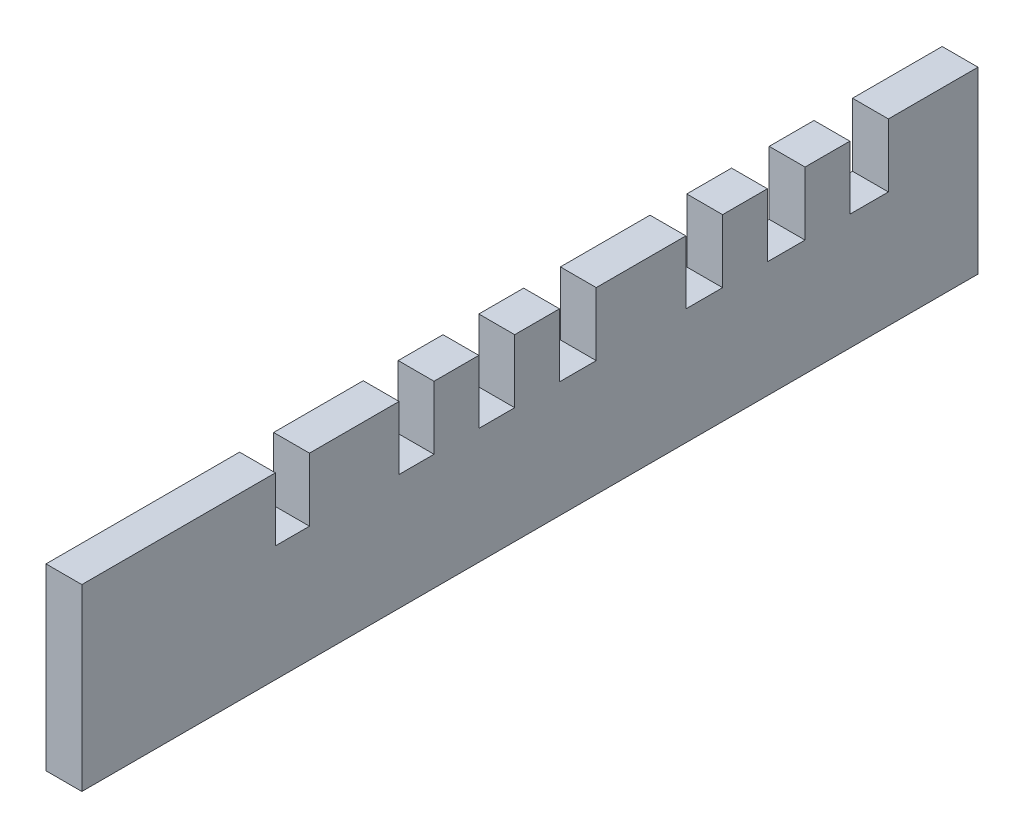
SolidWorks part; units mm, degrees
ref_plane "Front Plane" through (0, 0, 0) normal (0, 0, 1) x (1, 0, 0)
ref_plane "Top Plane" through (0, 0, 0) normal (0, 1, 0) x (1, 0, 0)
ref_plane "Right Plane" through (0, 0, 0) normal (1, 0, 0) x (0, 0, -1)
sketch "Sketch1" plane through (0, 0, 0) normal (0, 0, 1) x (1, 0, 0)
  line L1 (0, 0) -> (5.08, 0)
  line L2 (0, 0) -> (0, 25.4)
  line L3 (0, 25.4) -> (5.08, 25.4)
  line L4 (5.08, 0) -> (5.08, 25.4)
  dimension "D1" = 25.4
  dimension "D2" = 5.08
extrude "Boss-Extrude1" add sketch "Sketch1" along normal blind 127
sketch "Sketch8" plane through (0, 0, 0) normal (-1, 0, 0) x (0, 0, 1)
  text T0 ".215"
  text T1 ".195\r\n"
sketch "Sketch9" plane through (5.08, 0, 0) normal (1, 0, 0) x (0, 0, -1)
  line L0 (-127, 25.4) -> (0, 25.4) construction
  line L1 (-12.7, 25.4) -> (-18.161, 25.4)
  line L2 (-12.7, 25.4) -> (-12.7, 16.4345)
  line L3 (-12.7, 16.4345) -> (-18.161, 16.4345)
  line L4 (-18.161, 25.4) -> (-18.161, 16.4345)
  line L5 (0, 0) -> (0, 25.4) construction
  line L6 (-24.511, 25.4) -> (-29.845, 25.4)
  line L7 (-24.511, 25.4) -> (-24.511, 16.4345)
  line L8 (-24.511, 16.4345) -> (-29.845, 16.4345)
  line L9 (-29.845, 25.4) -> (-29.845, 16.4345)
  line L10 (-36.195, 25.4) -> (-41.402, 25.4)
  line L11 (-36.195, 25.4) -> (-36.195, 16.4345)
  line L12 (-36.195, 16.4345) -> (-41.402, 16.4345)
  line L13 (-41.402, 25.4) -> (-41.402, 16.4345)
  line L14 (-54.102, 25.4) -> (-59.309, 25.4)
  line L15 (-54.102, 25.4) -> (-54.102, 16.4345)
  line L16 (-54.102, 16.4345) -> (-59.309, 16.4345)
  line L17 (-59.309, 25.4) -> (-59.309, 16.4345)
  line L18 (-65.659, 25.4) -> (-70.739, 25.4)
  line L19 (-65.659, 25.4) -> (-65.659, 16.4345)
  line L20 (-65.659, 16.4345) -> (-70.739, 16.4345)
  line L21 (-70.739, 25.4) -> (-70.739, 16.4345)
  line L22 (-77.089, 25.4) -> (-82.042, 25.4)
  line L23 (-77.089, 25.4) -> (-77.089, 16.4345)
  line L24 (-77.089, 16.4345) -> (-82.042, 16.4345)
  line L25 (-82.042, 25.4) -> (-82.042, 16.4345)
  line L26 (-94.742, 25.4) -> (-99.568, 25.4)
  line L27 (-94.742, 25.4) -> (-94.742, 16.4345)
  line L28 (-94.742, 16.4345) -> (-99.568, 16.4345)
  line L29 (-99.568, 25.4) -> (-99.568, 16.4345)
  dimension "D1" = 5.461
  dimension "D2" = 5.334
  dimension "D3" = 5.207
  dimension "D4" = 5.207
  dimension "D5" = 5.08
  dimension "D6" = 4.953
  dimension "D7" = 4.826
  dimension "D8" = 12.7
  dimension "D9" = 6.35
  dimension "D10" = 6.35
  dimension "D11" = 12.7
  dimension "D12" = 6.35
  dimension "D13" = 6.35
  dimension "D14" = 12.7
extrude "Cut-Extrude1" cut sketch "Sketch9" against normal blind 12.7
